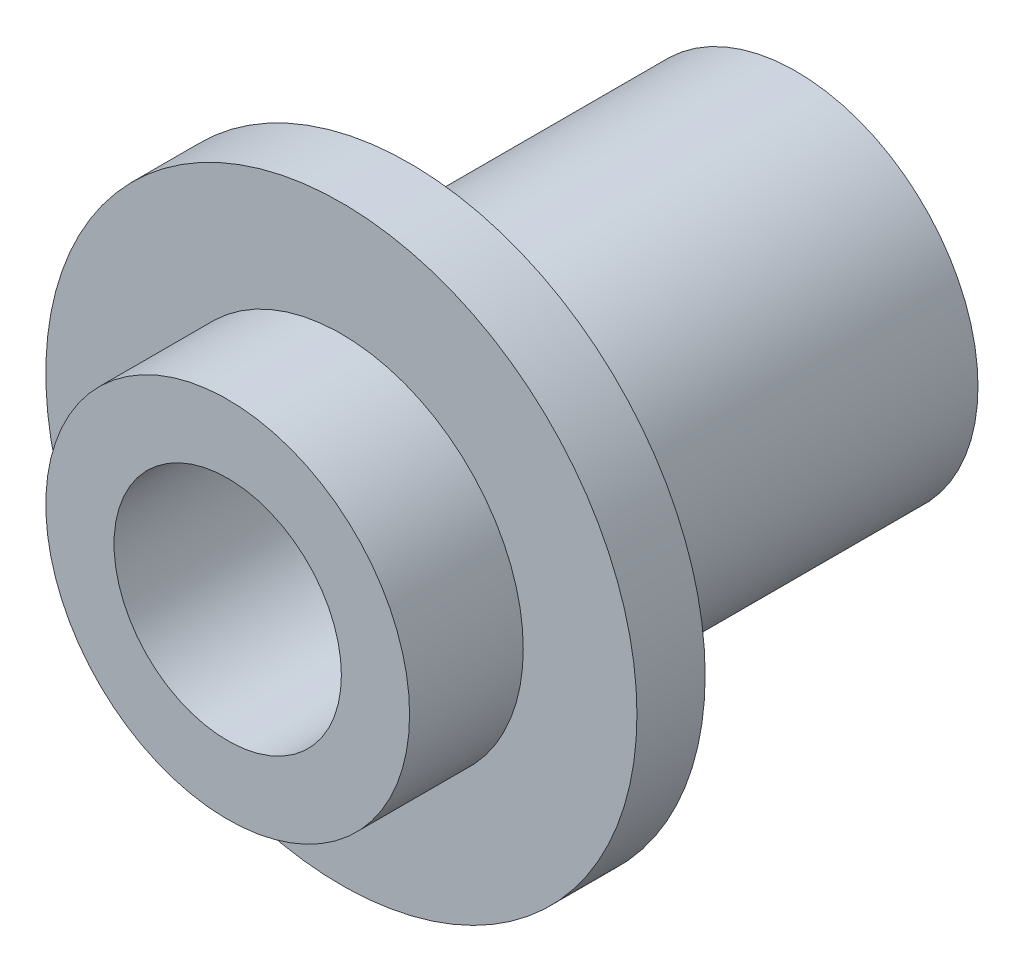
SolidWorks part; units mm, degrees
ref_plane "Front Plane" through (0, 0, 0) normal (0, 0, 1) x (1, 0, 0)
ref_plane "Top Plane" through (0, 0, 0) normal (0, 1, 0) x (1, 0, 0)
ref_plane "Right Plane" through (0, 0, 0) normal (1, 0, 0) x (0, 0, -1)
other "Configuration Table"
sketch "Sketch1" plane through (0, 0, 0) normal (1, 0, 0) x (0, 0, -1)
  line L0 (-5, 5) -> (-5, 8)
  line L1 (-5, 8) -> (0, 8)
  line L2 (0, 8) -> (0, 13)
  line L3 (0, 13) -> (3, 13)
  line L4 (3, 13) -> (3, 8)
  line L5 (3, 8) -> (20, 8)
  line L6 (20, 8) -> (20, 5)
  line L7 (20, 5) -> (-5, 5)
  line L8 (-30, 0) -> (40, 0) construction
  dimension "D1" = 8
  dimension "D2" = 5
  dimension "D3" = 13
  dimension "D4" = 5
  dimension "D5" = 3
  dimension "D6" = 25
revolve "Revolve1" add sketch "Sketch1" angle 360 about L8
